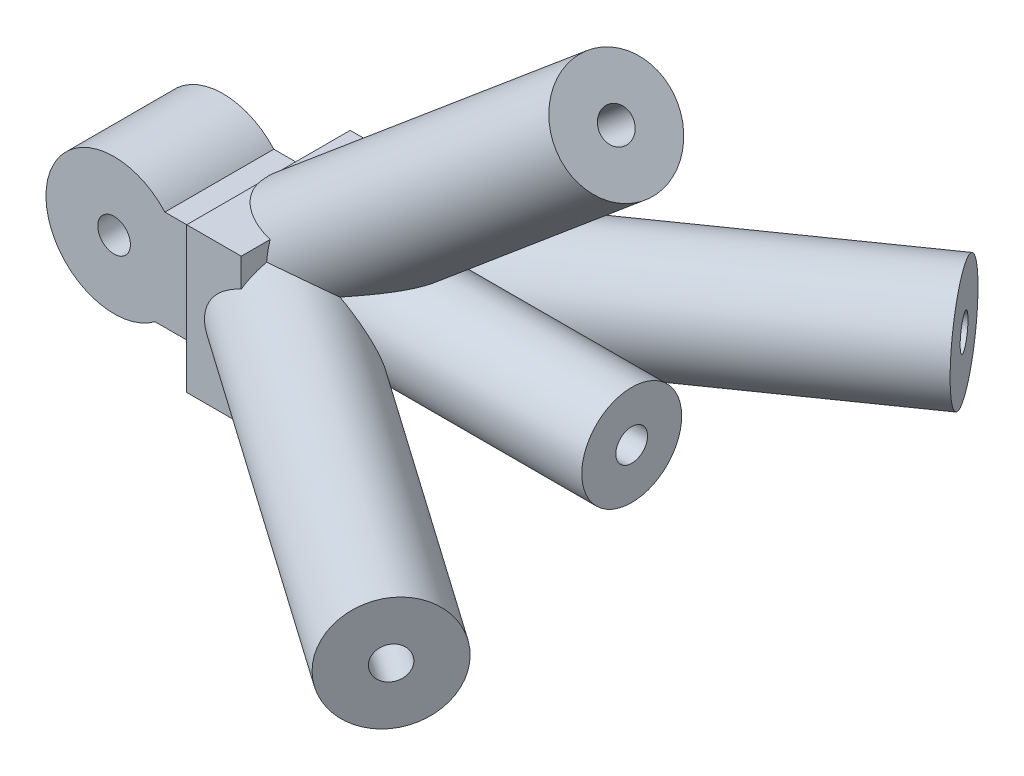
SolidWorks part; units mm, degrees
ref_plane "前视基准面" through (0, 0, 0) normal (0, 0, 1) x (1, 0, 0)
ref_plane "上视基准面" through (0, 0, 0) normal (0, 1, 0) x (1, 0, 0)
ref_plane "右视基准面" through (0, 0, 0) normal (1, 0, 0) x (0, 0, -1)
sketch "草图1" plane through (0, 0, 0) normal (0, 1, 0) x (1, 0, 0)
  line L0 (0, 0) -> (9.0107, 6.3093)
  line L1 (9.0107, 6.3093) -> (9.0107, -6.3093) construction
  line L2 (9.0107, -6.3093) -> (0, 0)
  line L3 (0, 0) -> (9.0107, 0) construction
  dimension "D1" = 11
  dimension "D2" = 35
sketch "草图2" plane through (0, 0, 0) normal (1, 0, 0) x (0, 0, -1)
  line L1 (-1.8, -1.6) -> (1.8, -1.6)
  line L2 (-1.8, -1.6) -> (-1.8, 1.6)
  line L3 (-1.8, 1.6) -> (1.8, 1.6)
  line L4 (1.8, -1.6) -> (1.8, 1.6)
  line L5 (-1.8, -1.6) -> (1.8, 1.6) construction
  line L6 (-1.8, 1.6) -> (1.8, -1.6) construction
  line L7 (-0.9562, -0.85) -> (0.9562, -0.85)
  line L8 (-0.9562, -0.85) -> (-0.9562, 0.85)
  line L9 (-0.9562, 0.85) -> (0.9562, 0.85)
  line L10 (0.9562, -0.85) -> (0.9562, 0.85)
  line L11 (-0.9562, -0.85) -> (0.9562, 0.85) construction
  line L12 (-0.9562, 0.85) -> (0.9562, -0.85) construction
  point P0 (0, 0)
  point P6 (0, 0)
  dimension "D1" = 3.2
  dimension "D2" = 1.7
  dimension "D3" = 3.6
extrude "凸台-拉伸1" add sketch "草图2" against normal blind 7
ref_plane "基准面1" through (9.0107, 0, 6.3093) normal (-0.8192, 0, -0.5736) x (-0.5736, 0, 0.8192)
sketch "草图3" plane through (9.0107, 0, 6.3093) normal (-0.8192, 0, -0.5736) x (-0.5736, 0, 0.8192)
  circle A0 centre (0, 0) radius 1.25
  circle A1 centre (0, 0) radius 0.36
  dimension "D1" = 2.5
  dimension "D2" = 0.72
extrude "凸台-拉伸2" add sketch "草图3" along normal up to surface (10.1247 mm away)
ref_plane "基准面2" through (9.0107, 0, -6.3093) normal (0.8192, 0, -0.5736) x (-0.5736, 0, -0.8192)
sketch "草图4" plane through (9.0107, 0, -6.3093) normal (0.8192, 0, -0.5736) x (-0.5736, 0, -0.8192)
  circle A0 centre (0, 0) radius 1.25
  circle A1 centre (0, 0) radius 0.35
  dimension "D1" = 0.7
  dimension "D2" = 2.5
extrude "凸台-拉伸3" add sketch "草图4" against normal up to surface (10.1247 mm away)
sketch "草图5" plane through (0, 0, 0) normal (1, 0, 0) x (0, 0, -1)
  line L4 (1.8, -1.6) -> (1.8, 1.6)
  line L5 (1.8, 1.6) -> (-1.8, 1.6)
  line L6 (-1.8, 1.6) -> (-1.8, -1.6)
  line L7 (-1.8, -1.6) -> (1.8, -1.6)
  line L8 (1.8, -1.6) -> (1.8, 1.6)
  line L9 (1.8, 1.6) -> (-1.8, 1.6)
  line L10 (-1.8, 1.6) -> (-1.8, -1.6)
  line L11 (-1.8, -1.6) -> (1.8, -1.6)
  dimension "D1" = 0
extrude "凸台-拉伸4" add sketch "草图5" along normal blind 1.2
sketch "草图6" plane through (-7, 0, 0) normal (-1, 0, 0) x (0, 0, 1)
  line L4 (-1.8, 1.6) -> (-1.8, -1.6)
  line L5 (-1.8, -1.6) -> (1.8, -1.6)
  line L6 (1.8, -1.6) -> (1.8, 1.6)
  line L7 (1.8, 1.6) -> (-1.8, 1.6)
  line L8 (-1.8, 1.6) -> (-1.8, -1.6)
  line L9 (-1.8, -1.6) -> (1.8, -1.6)
  line L10 (1.8, -1.6) -> (1.8, 1.6)
  line L11 (1.8, 1.6) -> (-1.8, 1.6)
  dimension "D1" = 0
extrude "切除-拉伸1" cut sketch "草图6" against normal up to surface (7 mm away)
sketch "草图7" plane through (0, 0, 0) normal (0, 0, 1) x (1, 0, 0)
  line L0 (-2.2, 0) -> (0, 0) construction
  line L1 (0, 1.6) -> (0, -1.6) construction
  line L2 (0, 1) -> (-1.082, 1)
  line L3 (0, 1) -> (0, -1.2)
  line L4 (0, -1.2) -> (-1.3, -1.2)
  arc A0 (-1.082, 1) -> (-1.3, -1.2) centre (-2.2, 0) ccw
  circle A1 centre (-2.2, 0) radius 0.36
  dimension "D1" = 0.72
  dimension "D2" = 1.5
  dimension "D3" = 2.2
  dimension "D4" = 2.2
  dimension "D5" = 1
extrude "凸台-拉伸5" add sketch "草图7" along normal mid plane 2.4
sketch "草图8" plane through (0, 0, 0) normal (0, 0, 1) x (1, 0, 0)
  line L0 (0, 0) -> (8, 0) construction
  line L1 (0, 0) -> (7.6604, 6.4279) construction
  line L2 (0, 1.5) -> (8, 1.5)
  dimension "D1" = 40
  dimension "D2" = 10
  dimension "D3" = 8
  dimension "D4" = 1.5
ref_plane "基准面3" through (7.6604, 6.4279, 0) normal (0.766, 0.6428, 0) x (0, 0, -1)
sketch "草图9" plane through (7.6604, 6.4279, 0) normal (0.766, 0.6428, 0) x (0, 0, -1)
  circle A0 centre (0, 0) radius 1.25
  circle A1 centre (0, 0) radius 0.35
  dimension "D1" = 0.7
  dimension "D2" = 2.5
extrude "凸台-拉伸6" add sketch "草图9" against normal up to surface (8.9511 mm away)
ref_plane "基准面4" through (8, 1.5, 0) normal (1, 0, 0) x (0, 0, -1)
sketch "草图10" plane through (8, 1.5, 0) normal (1, 0, 0) x (0, 0, -1)
  line L0 (0, -1.5) -> (0, 4.9279) construction
  line L1 (0, -1.5) -> (0, -1) construction
  circle A0 centre (0, -1) radius 1.1
  circle A1 centre (0, -1) radius 0.35
  dimension "D1" = 0.7
  dimension "D2" = 2.2
  dimension "D3" = 0.5
extrude "凸台-拉伸7" add sketch "草图10" against normal up to surface (6.4805 mm away)
